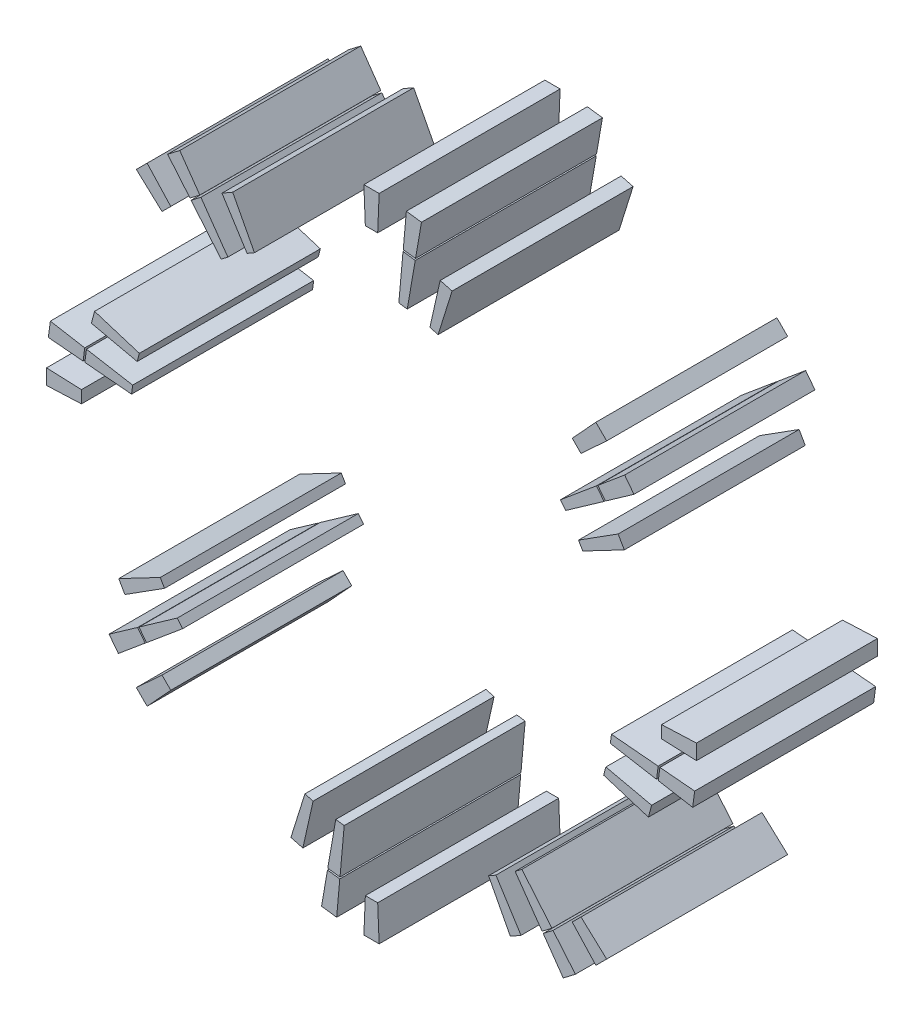
SolidWorks part; units mm, degrees
ref_plane "Спереди" through (0, 0, 0) normal (0, 0, 1) x (1, 0, 0)
ref_plane "Сверху" through (0, 0, 0) normal (0, 1, 0) x (1, 0, 0)
ref_plane "Справа" through (0, 0, 0) normal (1, 0, 0) x (0, 0, -1)
sketch "Эскиз1" plane through (0, 0, 0) normal (0, 0, 1) x (1, 0, 0)
  line L0 (64.1086, -1.3648) -> (71.8154, -1.6875)
  line L1 (71.8154, -1.6875) -> (71.8154, 1.6875)
  line L2 (71.8154, 1.6875) -> (64.1086, 1.3648)
  line L3 (64.1086, 1.3648) -> (64.1086, -1.3648)
  line L4 (46.6874, 25.8724) -> (55.8682, 30.6796)
  line L5 (55.8682, 30.6796) -> (54.5034, 33.0435)
  line L6 (54.5034, 33.0435) -> (45.7499, 27.4962)
  line L7 (45.7499, 27.4962) -> (46.6874, 25.8724)
  line L8 (51.6916, 37.9441) -> (58.0023, 42.3797)
  line L9 (58.0023, 42.3797) -> (55.9477, 45.0572)
  line L10 (55.9477, 45.0572) -> (50.0299, 40.1096)
  line L11 (50.0299, 40.1096) -> (51.6916, 37.9441)
  line L12 (42.9109, 31.745) -> (51.3857, 37.7094)
  line L13 (51.3857, 37.7094) -> (49.7241, 39.8749)
  line L14 (49.7241, 39.8749) -> (41.7695, 33.2326)
  line L15 (41.7695, 33.2326) -> (42.9109, 31.745)
  line L16 (46.2966, 44.3666) -> (51.9744, 49.5879)
  line L17 (51.9744, 49.5879) -> (49.5879, 51.9744)
  line L18 (49.5879, 51.9744) -> (44.3666, 46.2966)
  line L19 (44.3666, 46.2966) -> (46.2966, 44.3666)
  line L20 (14.7184, 51.3076) -> (17.811, 61.1985)
  line L21 (17.811, 61.1985) -> (15.1745, 61.905)
  line L22 (15.1745, 61.905) -> (12.9073, 51.7928)
  line L23 (12.9073, 51.7928) -> (14.7184, 51.3076)
  line L24 (9.7209, 63.382) -> (11.0469, 70.9807)
  line L25 (11.0469, 70.9807) -> (7.7007, 71.4213)
  line L26 (7.7007, 71.4213) -> (7.0147, 63.7382)
  line L27 (7.0147, 63.7382) -> (9.7209, 63.382)
  line L28 (7.8955, 52.7897) -> (9.6706, 62.9998)
  line L29 (9.6706, 62.9998) -> (6.9644, 63.3561)
  line L30 (6.9644, 63.3561) -> (6.0365, 53.0345)
  line L31 (6.0365, 53.0345) -> (7.8955, 52.7897)
  line L32 (1.3648, 64.1086) -> (1.6875, 71.8154)
  line L33 (1.6875, 71.8154) -> (-1.6875, 71.8154)
  line L34 (-1.6875, 71.8154) -> (-1.3648, 64.1086)
  line L35 (-1.3648, 64.1086) -> (1.3648, 64.1086)
  line L36 (-25.8724, 46.6874) -> (-30.6796, 55.8682)
  line L37 (-30.6796, 55.8682) -> (-33.0435, 54.5034)
  line L38 (-33.0435, 54.5034) -> (-27.4962, 45.7499)
  line L39 (-27.4962, 45.7499) -> (-25.8724, 46.6874)
  line L40 (-37.9441, 51.6916) -> (-42.3797, 58.0023)
  line L41 (-42.3797, 58.0023) -> (-45.0572, 55.9477)
  line L42 (-45.0572, 55.9477) -> (-40.1096, 50.0299)
  line L43 (-40.1096, 50.0299) -> (-37.9441, 51.6916)
  line L44 (-31.745, 42.9109) -> (-37.7094, 51.3857)
  line L45 (-37.7094, 51.3857) -> (-39.8749, 49.7241)
  line L46 (-39.8749, 49.7241) -> (-33.2326, 41.7695)
  line L47 (-33.2326, 41.7695) -> (-31.745, 42.9109)
  line L48 (-44.3666, 46.2966) -> (-49.5879, 51.9744)
  line L49 (-49.5879, 51.9744) -> (-51.9744, 49.5879)
  line L50 (-51.9744, 49.5879) -> (-46.2966, 44.3666)
  line L51 (-46.2966, 44.3666) -> (-44.3666, 46.2966)
  line L52 (-51.3076, 14.7184) -> (-61.1985, 17.811)
  line L53 (-61.1985, 17.811) -> (-61.905, 15.1745)
  line L54 (-61.905, 15.1745) -> (-51.7928, 12.9073)
  line L55 (-51.7928, 12.9073) -> (-51.3076, 14.7184)
  line L56 (-63.382, 9.7209) -> (-70.9807, 11.0469)
  line L57 (-70.9807, 11.0469) -> (-71.4213, 7.7007)
  line L58 (-71.4213, 7.7007) -> (-63.7382, 7.0147)
  line L59 (-63.7382, 7.0147) -> (-63.382, 9.7209)
  line L60 (-52.7897, 7.8955) -> (-62.9998, 9.6706)
  line L61 (-62.9998, 9.6706) -> (-63.3561, 6.9644)
  line L62 (-63.3561, 6.9644) -> (-53.0345, 6.0365)
  line L63 (-53.0345, 6.0365) -> (-52.7897, 7.8955)
  line L64 (-64.1086, 1.3648) -> (-71.8154, 1.6875)
  line L65 (-71.8154, 1.6875) -> (-71.8154, -1.6875)
  line L66 (-71.8154, -1.6875) -> (-64.1086, -1.3648)
  line L67 (-64.1086, -1.3648) -> (-64.1086, 1.3648)
  line L68 (-46.6874, -25.8724) -> (-55.8682, -30.6796)
  line L69 (-55.8682, -30.6796) -> (-54.5034, -33.0435)
  line L70 (-54.5034, -33.0435) -> (-45.7499, -27.4962)
  line L71 (-45.7499, -27.4962) -> (-46.6874, -25.8724)
  line L72 (-51.6916, -37.9441) -> (-58.0023, -42.3797)
  line L73 (-58.0023, -42.3797) -> (-55.9477, -45.0572)
  line L74 (-55.9477, -45.0572) -> (-50.0299, -40.1096)
  line L75 (-50.0299, -40.1096) -> (-51.6916, -37.9441)
  line L76 (-42.9109, -31.745) -> (-51.3857, -37.7094)
  line L77 (-51.3857, -37.7094) -> (-49.7241, -39.8749)
  line L78 (-49.7241, -39.8749) -> (-41.7695, -33.2326)
  line L79 (-41.7695, -33.2326) -> (-42.9109, -31.745)
  line L80 (-46.2966, -44.3666) -> (-51.9744, -49.5879)
  line L81 (-51.9744, -49.5879) -> (-49.5879, -51.9744)
  line L82 (-49.5879, -51.9744) -> (-44.3666, -46.2966)
  line L83 (-44.3666, -46.2966) -> (-46.2966, -44.3666)
  line L84 (-14.7184, -51.3076) -> (-17.811, -61.1985)
  line L85 (-17.811, -61.1985) -> (-15.1745, -61.905)
  line L86 (-15.1745, -61.905) -> (-12.9073, -51.7928)
  line L87 (-12.9073, -51.7928) -> (-14.7184, -51.3076)
  line L88 (-9.7209, -63.382) -> (-11.0469, -70.9807)
  line L89 (-11.0469, -70.9807) -> (-7.7007, -71.4213)
  line L90 (-7.7007, -71.4213) -> (-7.0147, -63.7382)
  line L91 (-7.0147, -63.7382) -> (-9.7209, -63.382)
  line L92 (-7.8955, -52.7897) -> (-9.6706, -62.9998)
  line L93 (-9.6706, -62.9998) -> (-6.9644, -63.3561)
  line L94 (-6.9644, -63.3561) -> (-6.0365, -53.0345)
  line L95 (-6.0365, -53.0345) -> (-7.8955, -52.7897)
  line L96 (-1.3648, -64.1086) -> (-1.6875, -71.8154)
  line L97 (-1.6875, -71.8154) -> (1.6875, -71.8154)
  line L98 (1.6875, -71.8154) -> (1.3648, -64.1086)
  line L99 (1.3648, -64.1086) -> (-1.3648, -64.1086)
  line L100 (25.8724, -46.6874) -> (30.6796, -55.8682)
  line L101 (30.6796, -55.8682) -> (33.0435, -54.5034)
  line L102 (33.0435, -54.5034) -> (27.4962, -45.7499)
  line L103 (27.4962, -45.7499) -> (25.8724, -46.6874)
  line L104 (37.9441, -51.6916) -> (42.3797, -58.0023)
  line L105 (42.3797, -58.0023) -> (45.0572, -55.9477)
  line L106 (45.0572, -55.9477) -> (40.1096, -50.0299)
  line L107 (40.1096, -50.0299) -> (37.9441, -51.6916)
  line L108 (31.745, -42.9109) -> (37.7094, -51.3857)
  line L109 (37.7094, -51.3857) -> (39.8749, -49.7241)
  line L110 (39.8749, -49.7241) -> (33.2326, -41.7695)
  line L111 (33.2326, -41.7695) -> (31.745, -42.9109)
  line L112 (44.3666, -46.2966) -> (49.5879, -51.9744)
  line L113 (49.5879, -51.9744) -> (51.9744, -49.5879)
  line L114 (51.9744, -49.5879) -> (46.2966, -44.3666)
  line L115 (46.2966, -44.3666) -> (44.3666, -46.2966)
  line L116 (51.3076, -14.7184) -> (61.1985, -17.811)
  line L117 (61.1985, -17.811) -> (61.905, -15.1745)
  line L118 (61.905, -15.1745) -> (51.7928, -12.9073)
  line L119 (51.7928, -12.9073) -> (51.3076, -14.7184)
  line L120 (63.382, -9.7209) -> (70.9807, -11.0469)
  line L121 (70.9807, -11.0469) -> (71.4213, -7.7007)
  line L122 (71.4213, -7.7007) -> (63.7382, -7.0147)
  line L123 (63.7382, -7.0147) -> (63.382, -9.7209)
  line L124 (52.7897, -7.8955) -> (62.9998, -9.6706)
  line L125 (62.9998, -9.6706) -> (63.3561, -6.9644)
  line L126 (63.3561, -6.9644) -> (53.0345, -6.0365)
  line L127 (53.0345, -6.0365) -> (52.7897, -7.8955)
extrude "Slot_copper_envelopes" add sketch "Эскиз1" along normal blind 40 from offset 20 separate body
